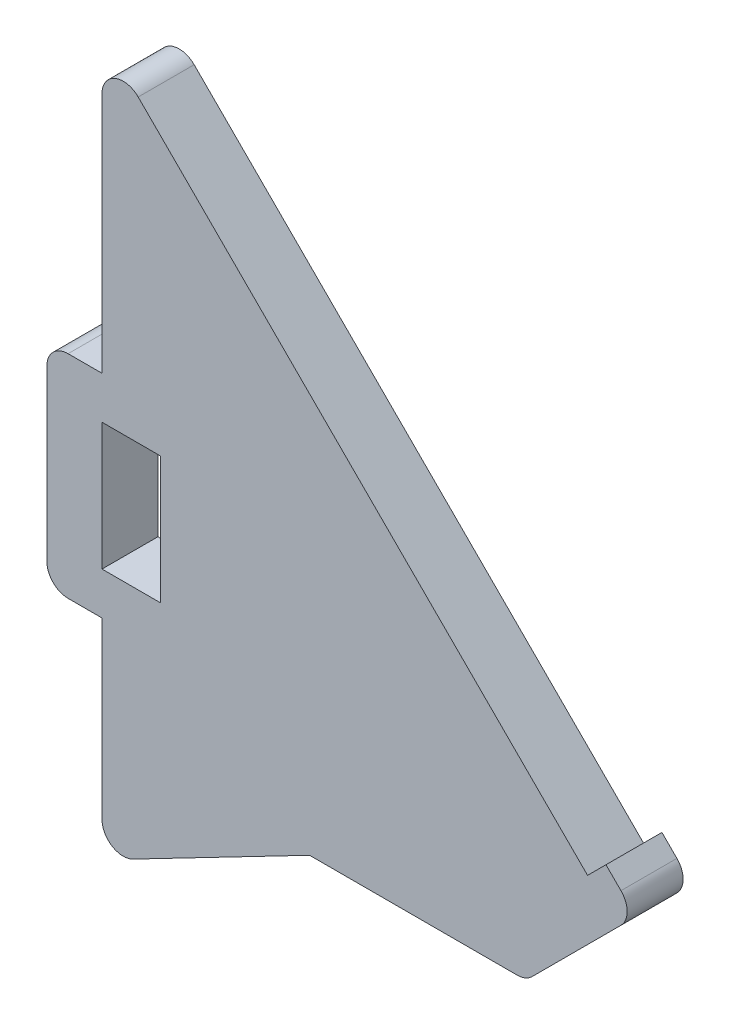
SolidWorks part; units mm, degrees
ref_plane "Front Plane" through (0, 0, 0) normal (0, 0, 1) x (1, 0, 0)
ref_plane "Top Plane" through (0, 0, 0) normal (0, 1, 0) x (1, 0, 0)
ref_plane "Right Plane" through (0, 0, 0) normal (1, 0, 0) x (0, 0, -1)
sketch "Model" plane through (0, 0, 0) normal (0, 0, 1) x (1, 0, 0)
  line L0 (0, -59.6224) -> (-4, -59.6224)
  line L1 (-6.5, -57.1224) -> (-6.5, -37.1224)
  line L2 (-4, -34.6224) -> (0, -34.6224)
  line L3 (57.2756, -57.2756) -> (4.2678, -4.2678)
  line L4 (59.4465, -55.1048) -> (57.2756, -57.2756)
  line L5 (61.2142, -56.8726) -> (59.4465, -55.1048)
  line L6 (50.7322, -70.8901) -> (61.2142, -60.4081)
  line L7 (24.4822, -71.6224) -> (48.9645, -71.6224)
  line L8 (24.4822, -71.6224) -> (3.6512, -82.4283)
  line L9 (6.88, -39.6224) -> (0, -39.6224)
  line L10 (0, -39.6224) -> (0, -54.6224)
  line L11 (0, -54.6224) -> (6.88, -54.6224)
  line L12 (6.88, -54.6224) -> (6.88, -39.6224)
  line L13 (0, -59.6224) -> (0, -80.2092)
  line L14 (0, -6.0355) -> (0, -34.6224)
  arc A0 (-6.5, -57.1224) -> (-4, -59.6224) centre (-4, -57.1224) ccw
  arc A1 (-4, -34.6224) -> (-6.5, -37.1224) centre (-4, -37.1224) ccw
  arc A2 (4.2678, -4.2678) -> (0, -6.0355) centre (2.5, -6.0355) ccw
  arc A3 (61.2142, -60.4081) -> (61.2142, -56.8726) centre (59.4465, -58.6404) ccw
  arc A4 (48.9645, -71.6224) -> (50.7322, -70.8901) centre (48.9645, -69.1224) ccw
  arc A5 (0, -80.2092) -> (3.6512, -82.4283) centre (2.5, -80.2092) ccw
extrude "Boss-Extrude1" add sketch "Model" along normal blind 6.6
